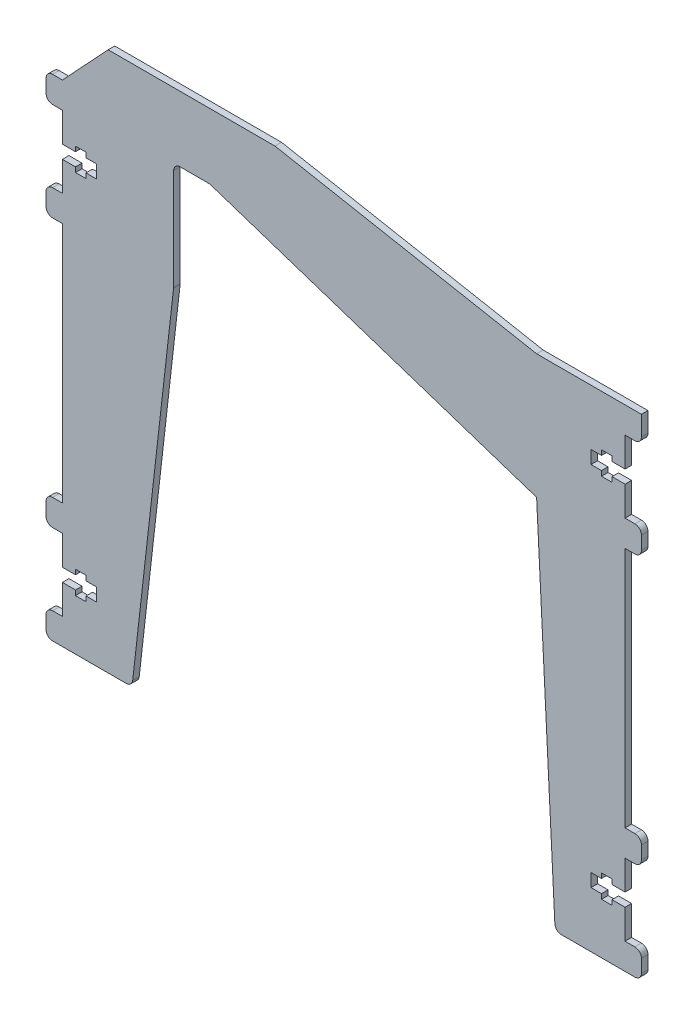
SolidWorks part; units mm, degrees
ref_plane "前视基准面" through (0, 0, 0) normal (0, 0, 1) x (1, 0, 0)
ref_plane "上视基准面" through (0, 0, 0) normal (0, 1, 0) x (1, 0, 0)
ref_plane "右视基准面" through (0, 0, 0) normal (1, 0, 0) x (0, 0, -1)
sketch "草图1" plane through (0, 0, 0) normal (0, 0, 1) x (1, 0, 0)
  line L0 (81.606, 5.4175) -> (76.6694, 5.4175) construction
  line L1 (81.606, 35.4175) -> (76.6694, 35.4175) construction
  line L2 (81.606, 9.4175) -> (76.606, 9.4175)
  line L3 (81.606, 1.4175) -> (81.606, 9.4175)
  line L4 (76.606, 1.4175) -> (81.606, 1.4175)
  line L5 (66.206, 20.4175) -> (166.1289, 20.4175) construction
  line L6 (76.606, 22.4175) -> (72.606, 22.4175)
  line L7 (72.606, 22.4175) -> (72.606, 23.9175)
  line L8 (72.606, 23.9175) -> (69.406, 23.9175)
  line L9 (69.406, 23.9175) -> (69.406, 22.4175)
  line L10 (69.406, 22.4175) -> (66.206, 22.4175)
  line L11 (69.406, 16.9175) -> (69.406, 18.4175)
  line L12 (72.606, 18.4175) -> (72.606, 16.9175)
  line L13 (69.406, 18.4175) -> (66.206, 18.4175)
  line L14 (72.606, 16.9175) -> (69.406, 16.9175)
  line L15 (76.606, 18.4175) -> (72.606, 18.4175)
  line L16 (76.606, 39.4175) -> (81.606, 39.4175)
  line L17 (81.606, 39.4175) -> (81.606, 31.4175)
  line L18 (81.606, 31.4175) -> (76.606, 31.4175)
  line L19 (76.606, 31.4175) -> (76.606, 22.4175)
  line L20 (76.606, 9.4175) -> (76.606, 18.4175)
  line L21 (76.606, 22.4175) -> (72.606, 22.4175)
  line L22 (72.606, 23.9175) -> (69.406, 23.9175)
  line L23 (76.606, 22.4175) -> (72.606, 22.4175)
  line L24 (72.606, 22.4175) -> (72.606, 23.9175)
  line L25 (72.606, 23.9175) -> (69.406, 23.9175)
  line L26 (69.406, 23.9175) -> (69.406, 22.4175)
  line L27 (69.406, 22.4175) -> (66.206, 22.4175)
  line L28 (69.406, 16.9175) -> (69.406, 18.4175)
  line L29 (72.606, 18.4175) -> (72.606, 16.9175)
  line L30 (69.406, 18.4175) -> (66.206, 18.4175)
  line L31 (72.606, 16.9175) -> (69.406, 16.9175)
  line L32 (76.606, 18.4175) -> (72.606, 18.4175)
  line L33 (69.406, 22.4175) -> (66.206, 22.4175)
  line L34 (72.606, 22.4175) -> (72.606, 23.9175)
  line L35 (69.406, 23.9175) -> (69.406, 22.4175)
  line L36 (69.406, 18.4175) -> (66.206, 18.4175)
  line L37 (69.406, 16.9175) -> (69.406, 18.4175)
  line L38 (72.606, 16.9175) -> (69.406, 16.9175)
  line L39 (72.606, 18.4175) -> (72.606, 16.9175)
  line L40 (76.606, 18.4175) -> (72.606, 18.4175)
  line L41 (76.606, 39.4175) -> (49.5687, 39.4175)
  line L42 (-61.394, 1.4175) -> (-74.1101, -110.5825)
  line L43 (-9.394, 39.4175) -> (-9.394, -22.62) construction
  line L44 (76.606, 1.4175) -> (76.606, -72.5825)
  line L45 (-100.394, 35.4175) -> (-95.4574, 35.4175) construction
  line L46 (-100.394, 5.4175) -> (-95.4574, 5.4175) construction
  line L47 (-95.394, 18.4175) -> (-91.394, 18.4175)
  line L48 (-91.394, 18.4175) -> (-91.394, 16.9175)
  line L49 (-91.394, 16.9175) -> (-88.194, 16.9175)
  line L50 (-88.194, 16.9175) -> (-88.194, 18.4175)
  line L51 (-88.194, 18.4175) -> (-84.994, 18.4175)
  line L52 (-84.994, 18.4175) -> (-84.994, 22.4175)
  line L53 (-88.194, 23.9175) -> (-88.194, 22.4175)
  line L54 (-91.394, 22.4175) -> (-91.394, 23.9175)
  line L55 (-88.194, 22.4175) -> (-84.994, 22.4175)
  line L56 (-91.394, 23.9175) -> (-88.194, 23.9175)
  line L57 (-95.394, 22.4175) -> (-91.394, 22.4175)
  line L58 (76.606, 22.4175) -> (72.606, 22.4175)
  line L59 (72.606, 23.9175) -> (69.406, 23.9175)
  line L60 (69.406, 22.4175) -> (66.206, 22.4175)
  line L61 (72.606, 22.4175) -> (72.606, 23.9175)
  line L62 (69.406, 23.9175) -> (69.406, 22.4175)
  line L63 (66.206, 18.4175) -> (66.206, 22.4175)
  line L64 (69.406, 18.4175) -> (66.206, 18.4175)
  line L65 (69.406, 16.9175) -> (69.406, 18.4175)
  line L66 (72.606, 16.9175) -> (69.406, 16.9175)
  line L67 (72.606, 18.4175) -> (72.606, 16.9175)
  line L68 (76.606, 18.4175) -> (72.606, 18.4175)
  line L69 (-95.394, 18.4175) -> (-91.394, 18.4175)
  line L70 (-91.394, 18.4175) -> (-91.394, 16.9175)
  line L71 (-91.394, 16.9175) -> (-88.194, 16.9175)
  line L72 (-88.194, 16.9175) -> (-88.194, 18.4175)
  line L73 (-88.194, 18.4175) -> (-84.994, 18.4175)
  line L74 (-88.194, 23.9175) -> (-88.194, 22.4175)
  line L76 (-91.394, 22.4175) -> (-91.394, 23.9175)
  line L78 (-88.194, 22.4175) -> (-84.994, 22.4175)
  line L79 (-95.394, 18.4175) -> (-91.394, 18.4175)
  line L81 (-91.394, 16.9175) -> (-88.194, 16.9175)
  line L82 (-88.194, 18.4175) -> (-84.994, 18.4175)
  line L84 (-91.394, 18.4175) -> (-91.394, 16.9175)
  line L85 (-88.194, 16.9175) -> (-88.194, 18.4175)
  line L87 (-88.194, 22.4175) -> (-84.994, 22.4175)
  line L88 (-88.194, 23.9175) -> (-88.194, 22.4175)
  line L89 (-91.394, 23.9175) -> (-88.194, 23.9175)
  line L90 (-91.394, 22.4175) -> (-91.394, 23.9175)
  line L92 (-95.394, 22.4175) -> (-91.394, 22.4175)
  line L94 (-91.394, 23.9175) -> (-88.194, 23.9175)
  line L95 (-95.394, 22.4175) -> (-91.394, 22.4175)
  line L97 (-95.394, 9.4175) -> (-95.394, 18.4175)
  line L98 (-95.394, 31.4175) -> (-95.394, 22.4175)
  line L99 (-100.394, 31.4175) -> (-95.394, 31.4175)
  line L100 (-100.394, 39.4175) -> (-100.394, 31.4175)
  line L101 (-95.394, 39.4175) -> (-100.394, 39.4175)
  line L102 (-95.394, 18.4175) -> (-91.394, 18.4175)
  line L104 (-91.394, 16.9175) -> (-88.194, 16.9175)
  line L105 (-88.194, 18.4175) -> (-84.994, 18.4175)
  line L107 (-91.394, 18.4175) -> (-91.394, 16.9175)
  line L108 (-88.194, 16.9175) -> (-88.194, 18.4175)
  line L109 (-88.194, 22.4175) -> (-84.994, 22.4175)
  line L110 (-88.194, 23.9175) -> (-88.194, 22.4175)
  line L111 (-91.394, 23.9175) -> (-88.194, 23.9175)
  line L112 (-91.394, 22.4175) -> (-91.394, 23.9175)
  line L113 (-95.394, 22.4175) -> (-91.394, 22.4175)
  line L114 (-95.394, 1.4175) -> (76.606, 1.4175) construction
  line L115 (-95.394, 1.4175) -> (-100.394, 1.4175)
  line L116 (-100.394, 1.4175) -> (-100.394, 9.4175)
  line L117 (-100.394, 9.4175) -> (-95.394, 9.4175)
  line L118 (-61.394, 1.4175) -> (-61.394, 34.4175)
  line L119 (-61.394, 34.4175) -> (-50.394, 34.4175)
  line L120 (49.5687, 1.4175) -> (-50.394, 34.4175)
  line L121 (53.2127, -35.5825) -> (113.6173, -35.5825) construction
  line L122 (55.2413, -110.5825) -> (49.5687, 1.4175)
  line L123 (-100.394, -76.5825) -> (-95.4574, -76.5825) construction
  line L124 (-100.394, -106.5825) -> (-95.4574, -106.5825) construction
  line L125 (-74.1101, -110.5825) -> (-95.394, -110.5825)
  line L126 (-95.394, -72.5825) -> (-95.394, 1.4175)
  line L127 (81.606, -106.5825) -> (76.6694, -106.5825) construction
  line L128 (81.606, -76.5825) -> (76.6694, -76.5825) construction
  line L129 (76.606, -110.5825) -> (55.2413, -110.5825)
  line L130 (49.5687, 39.4175) -> (-30.394, 54.4175)
  line L131 (-81.394, 54.4175) -> (-95.394, 39.4175)
  line L132 (-30.394, 54.4175) -> (-81.394, 54.4175)
  line L133 (-100.394, -80.5825) -> (-95.394, -80.5825)
  line L134 (-100.394, -72.5825) -> (-100.394, -80.5825)
  line L135 (-95.394, -72.5825) -> (-100.394, -72.5825)
  line L136 (-95.394, -93.5825) -> (-91.394, -93.5825)
  line L137 (-91.394, -93.5825) -> (-91.394, -95.0825)
  line L138 (-91.394, -95.0825) -> (-88.194, -95.0825)
  line L139 (-88.194, -95.0825) -> (-88.194, -93.5825)
  line L140 (-88.194, -93.5825) -> (-84.994, -93.5825)
  line L141 (-88.194, -88.0825) -> (-88.194, -89.5825)
  line L142 (-91.394, -89.5825) -> (-91.394, -88.0825)
  line L143 (-88.194, -89.5825) -> (-84.994, -89.5825)
  line L144 (-91.394, -88.0825) -> (-88.194, -88.0825)
  line L145 (-95.394, -89.5825) -> (-91.394, -89.5825)
  line L146 (-95.394, -110.5825) -> (-100.394, -110.5825)
  line L147 (-100.394, -110.5825) -> (-100.394, -102.5825)
  line L148 (-100.394, -102.5825) -> (-95.394, -102.5825)
  line L149 (-95.394, -102.5825) -> (-95.394, -93.5825)
  line L150 (-95.394, -80.5825) -> (-95.394, -89.5825)
  line L151 (-95.394, -93.5825) -> (-91.394, -93.5825)
  line L152 (-91.394, -95.0825) -> (-88.194, -95.0825)
  line L153 (-95.394, -93.5825) -> (-91.394, -93.5825)
  line L154 (-91.394, -93.5825) -> (-91.394, -95.0825)
  line L155 (-91.394, -95.0825) -> (-88.194, -95.0825)
  line L156 (-88.194, -95.0825) -> (-88.194, -93.5825)
  line L157 (-88.194, -93.5825) -> (-84.994, -93.5825)
  line L158 (-88.194, -88.0825) -> (-88.194, -89.5825)
  line L159 (-91.394, -89.5825) -> (-91.394, -88.0825)
  line L160 (-88.194, -89.5825) -> (-84.994, -89.5825)
  line L161 (-91.394, -88.0825) -> (-88.194, -88.0825)
  line L162 (-95.394, -89.5825) -> (-91.394, -89.5825)
  line L163 (-88.194, -93.5825) -> (-84.994, -93.5825)
  line L164 (-91.394, -93.5825) -> (-91.394, -95.0825)
  line L165 (-88.194, -95.0825) -> (-88.194, -93.5825)
  line L166 (-88.194, -89.5825) -> (-84.994, -89.5825)
  line L167 (-88.194, -88.0825) -> (-88.194, -89.5825)
  line L168 (-91.394, -88.0825) -> (-88.194, -88.0825)
  line L169 (-91.394, -89.5825) -> (-91.394, -88.0825)
  line L170 (-95.394, -89.5825) -> (-91.394, -89.5825)
  line L171 (76.606, -89.5825) -> (72.606, -89.5825)
  line L172 (72.606, -89.5825) -> (72.606, -88.0825)
  line L173 (72.606, -88.0825) -> (69.406, -88.0825)
  line L174 (69.406, -88.0825) -> (69.406, -89.5825)
  line L175 (69.406, -89.5825) -> (66.206, -89.5825)
  line L176 (66.206, -89.5825) -> (66.206, -93.5825)
  line L177 (69.406, -95.0825) -> (69.406, -93.5825)
  line L178 (72.606, -93.5825) -> (72.606, -95.0825)
  line L179 (69.406, -93.5825) -> (66.206, -93.5825)
  line L180 (72.606, -95.0825) -> (69.406, -95.0825)
  line L181 (76.606, -93.5825) -> (72.606, -93.5825)
  line L182 (-95.394, -93.5825) -> (-91.394, -93.5825)
  line L183 (-91.394, -95.0825) -> (-88.194, -95.0825)
  line L184 (-88.194, -93.5825) -> (-84.994, -93.5825)
  line L185 (-91.394, -93.5825) -> (-91.394, -95.0825)
  line L186 (-88.194, -95.0825) -> (-88.194, -93.5825)
  line L187 (-84.994, -89.5825) -> (-84.994, -93.5825)
  line L188 (-88.194, -89.5825) -> (-84.994, -89.5825)
  line L189 (-88.194, -88.0825) -> (-88.194, -89.5825)
  line L190 (-91.394, -88.0825) -> (-88.194, -88.0825)
  line L191 (-91.394, -89.5825) -> (-91.394, -88.0825)
  line L192 (-95.394, -89.5825) -> (-91.394, -89.5825)
  line L195 (76.606, -89.5825) -> (72.606, -89.5825)
  line L196 (72.606, -89.5825) -> (72.606, -88.0825)
  line L197 (72.606, -88.0825) -> (69.406, -88.0825)
  line L198 (69.406, -88.0825) -> (69.406, -89.5825)
  line L199 (69.406, -89.5825) -> (66.206, -89.5825)
  line L200 (69.406, -95.0825) -> (69.406, -93.5825)
  line L201 (72.606, -93.5825) -> (72.606, -95.0825)
  line L202 (69.406, -93.5825) -> (66.206, -93.5825)
  line L203 (76.606, -89.5825) -> (72.606, -89.5825)
  line L204 (72.606, -88.0825) -> (69.406, -88.0825)
  line L205 (69.406, -89.5825) -> (66.206, -89.5825)
  line L206 (72.606, -89.5825) -> (72.606, -88.0825)
  line L207 (69.406, -88.0825) -> (69.406, -89.5825)
  line L208 (69.406, -93.5825) -> (66.206, -93.5825)
  line L209 (69.406, -95.0825) -> (69.406, -93.5825)
  line L210 (72.606, -95.0825) -> (69.406, -95.0825)
  line L211 (72.606, -93.5825) -> (72.606, -95.0825)
  line L212 (76.606, -93.5825) -> (72.606, -93.5825)
  line L213 (72.606, -95.0825) -> (69.406, -95.0825)
  line L214 (76.606, -93.5825) -> (72.606, -93.5825)
  line L215 (76.606, -80.5825) -> (76.606, -89.5825)
  line L216 (76.606, -102.5825) -> (76.606, -93.5825)
  line L217 (81.606, -102.5825) -> (76.606, -102.5825)
  line L218 (81.606, -110.5825) -> (81.606, -102.5825)
  line L219 (76.606, -110.5825) -> (81.606, -110.5825)
  line L220 (76.606, -89.5825) -> (72.606, -89.5825)
  line L221 (72.606, -88.0825) -> (69.406, -88.0825)
  line L222 (69.406, -89.5825) -> (66.206, -89.5825)
  line L223 (72.606, -89.5825) -> (72.606, -88.0825)
  line L224 (69.406, -88.0825) -> (69.406, -89.5825)
  line L225 (69.406, -93.5825) -> (66.206, -93.5825)
  line L226 (69.406, -95.0825) -> (69.406, -93.5825)
  line L227 (72.606, -95.0825) -> (69.406, -95.0825)
  line L228 (72.606, -93.5825) -> (72.606, -95.0825)
  line L229 (76.606, -93.5825) -> (72.606, -93.5825)
  line L230 (76.606, -72.5825) -> (81.606, -72.5825)
  line L231 (81.606, -72.5825) -> (81.606, -80.5825)
  line L232 (81.606, -80.5825) -> (76.606, -80.5825)
  dimension "D1" = 172
  dimension "D2" = 7
  dimension "D3" = 4
  dimension "D4" = 8
  dimension "D5" = 4
  dimension "D6" = 3.2
  dimension "D7" = 5
  dimension "D8" = 15
  dimension "D9" = 34
  dimension "D10" = 56
  dimension "D11" = 33
  dimension "D14" = 20
  dimension "D15" = 11
extrude "凸台-拉伸1" add sketch "草图1" along normal blind 2
sketch "草图2" plane through (76.606, 0, 0) normal (1, 0, 0) x (0, 0, -1)
  line L0 (-1, 18.4175) -> (-1, 22.4175)
  line L1 (-2, 18.4175) -> (0, 18.4175) construction
  line L2 (-2, 22.4175) -> (0, 22.4175) construction
  circle A0 centre (-1, 20.4175) radius 2
fillet "圆角1" radius 2 19 edges at (81.606, 9.4175, 1) (81.606, 31.4175, 1) (81.606, 1.4175, 1) (81.606, -102.5825, 1) (81.606, -72.5825, 1) (-100.394, -102.5825, 1) (-100.394, -72.5825, 1) (-100.394, 9.4175, 1) (81.606, -80.5825, 1) (81.606, -110.5825, 1) (-100.394, 31.4175, 1) (-100.394, 1.4175, 1) (-100.394, -80.5825, 1) (-100.394, -110.5825, 1) (-74.1101, -110.5825, 1) (55.2413, -110.5825, 1) (-61.394, 1.4175, 1) (-61.394, 34.4175, 1) (-100.394, 39.4175, 1)
